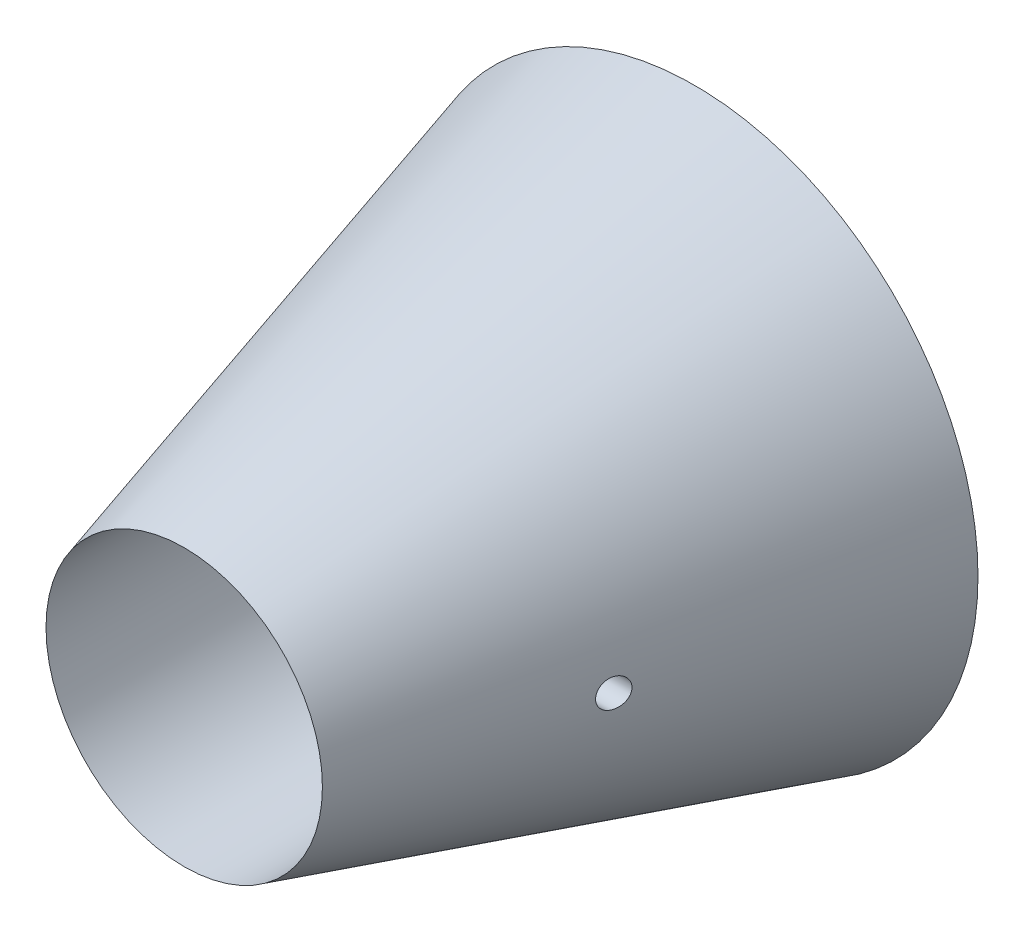
SolidWorks part; units mm, degrees
ref_plane "Plan de face" through (0, 0, 0) normal (0, 0, 1) x (1, 0, 0)
ref_plane "Plan de dessus" through (0, 0, 0) normal (0, 1, 0) x (1, 0, 0)
ref_plane "Plan de droite" through (0, 0, 0) normal (1, 0, 0) x (0, 0, -1)
sketch "Esquisse1" plane through (0, 0, 0) normal (0, 0, 1) x (1, 0, 0)
  circle A0 centre (0, 0) radius 100
  circle A1 centre (0, 0) radius 48.75
  dimension "D1" = 200
  dimension "D2" = 97.5
ref_plane "Plan1" through (0, 0, 180) normal (0, 0, 1) x (1, 0, 0)
sketch "Esquisse2" plane through (0, 0, 180) normal (0, 0, 1) x (1, 0, 0)
  circle A0 centre (0, 0) radius 48.75
  dimension "D1" = 97.5
sketch "Esquisse4" plane through (0, 0, 0) normal (1, 0, 0) x (0, 0, -1)
  line L0 (-180, 48.75) -> (0, 100)
  line L6 (-180, 48.75) -> (0, 48.75)
  line L9 (0, 48.75) -> (0, 100)
ref_axis "Axe1" through (0, 0, 180) along (0, 0, -1)
revolve "Révolution1" add sketch "Esquisse4" angle 360 about axis through (0, 0, 180) along (0, 0, -1)
ref_plane "Plan2" through (0, 0, 100) normal (0, 0, 1) x (1, 0, 0)
sketch "Esquisse6" plane through (0, 0, 100) normal (0, 0, 1) x (1, 0, 0)
  line L0 (0, 0) -> (274.7687, 64.6899)
sketch "Esquisse7" plane through (0, 0, 0) normal (1, 0, 0) x (0, 0, -1)
  circle A0 centre (-100, 0) radius 5
  dimension "D1" = 10
extrude "Enlèv. mat.-Extru.1" cut sketch "Esquisse7" along normal up to surface (72.9514 mm away) contours A0
